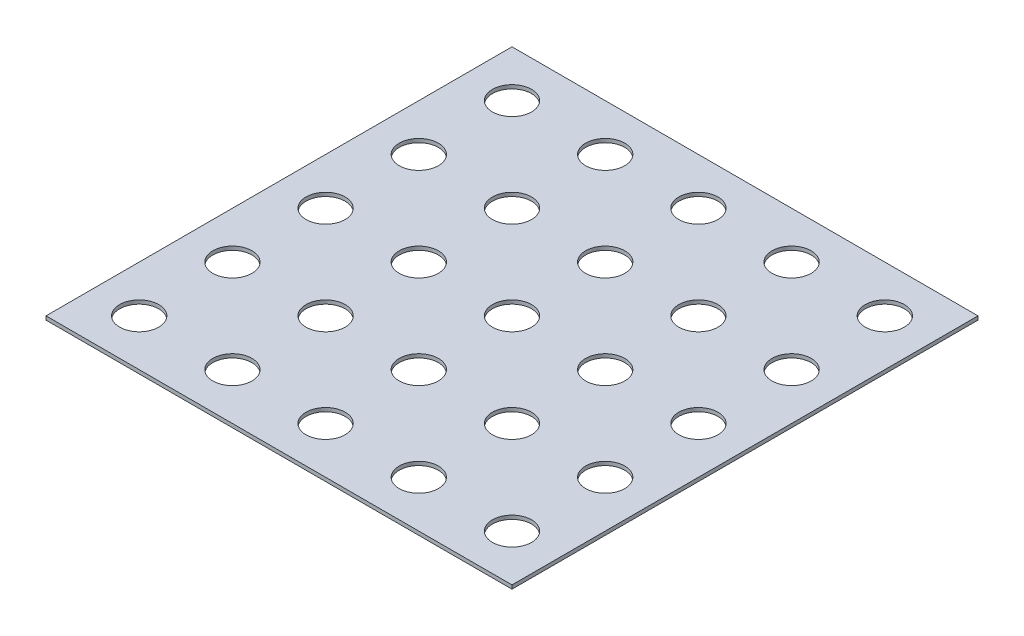
SolidWorks part; units mm, degrees
ref_plane "Front Plane" through (0, 0, 0) normal (0, 0, 1) x (1, 0, 0)
ref_plane "Top Plane" through (0, 0, 0) normal (0, 1, 0) x (1, 0, 0)
ref_plane "Right Plane" through (0, 0, 0) normal (1, 0, 0) x (0, 0, -1)
sketch "Sketch1" plane through (0, 0, 0) normal (0, 1, 0) x (1, 0, 0)
  line L1 (-125, 125) -> (125, 125)
  line L2 (-125, 125) -> (-125, -125)
  line L3 (-125, -125) -> (125, -125)
  line L4 (125, 125) -> (125, -125)
  point P4 (0, 125)
  point P6 (-125, 0)
  dimension "D1" = 250
extrude "Boss-Extrude1" add sketch "Sketch1" along normal blind 2
sketch "Sketch2" plane through (0, 2, 0) normal (0, 1, 0) x (1, 0, 0)
  line L0 (125, 125) -> (-125, 125) construction
  line L2 (-100, 125) -> (-100, 100) construction
  line L3 (-100, 100) -> (-125, 100) construction
  line L4 (-125, 125) -> (-125, -125) construction
  circle A0 centre (-100, 100) radius 10.5
  circle A1 centre (-50, 100) radius 10.5
  circle A2 centre (0, 100) radius 10.5
  circle A3 centre (50, 100) radius 10.5
  circle A4 centre (100, 100) radius 10.5
  circle A5 centre (-50, 50) radius 10.5
  circle A6 centre (0, 50) radius 10.5
  circle A7 centre (50, 50) radius 10.5
  circle A8 centre (100, 50) radius 10.5
  circle A9 centre (-50, 0) radius 10.5
  circle A10 centre (0, 0) radius 10.5
  circle A11 centre (50, 0) radius 10.5
  circle A12 centre (100, 0) radius 10.5
  circle A13 centre (-50, -50) radius 10.5
  circle A14 centre (0, -50) radius 10.5
  circle A15 centre (50, -50) radius 10.5
  circle A16 centre (100, -50) radius 10.5
  circle A17 centre (-50, -100) radius 10.5
  circle A18 centre (0, -100) radius 10.5
  circle A19 centre (50, -100) radius 10.5
  circle A20 centre (100, -100) radius 10.5
  circle A21 centre (-100, 50) radius 10.5
  circle A22 centre (-100, 0) radius 10.5
  circle A23 centre (-100, -50) radius 10.5
  circle A24 centre (-100, -100) radius 10.5
  dimension "D1" = 21
  dimension "D4" = 25
  dimension "D2" = 5
  dimension "D3" = 5
extrude "Cut-Extrude1" cut sketch "Sketch2" against normal through all
